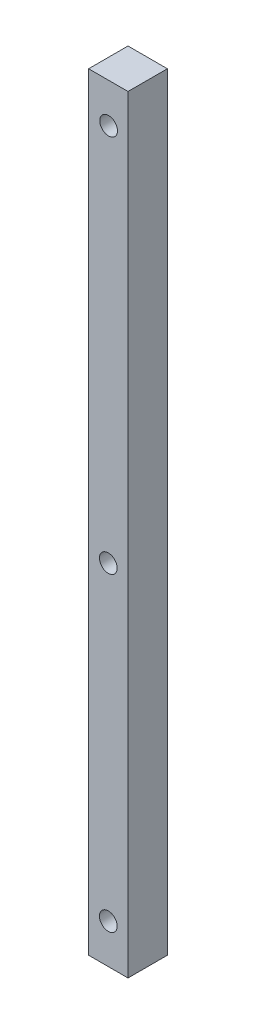
SolidWorks part; units mm, degrees
material "7075-T6, Plate (SS)"
ref_plane "Front Plane" through (0, 0, 0) normal (0, 0, 1) x (1, 0, 0)
ref_plane "Top Plane" through (0, 0, 0) normal (0, 1, 0) x (1, 0, 0)
ref_plane "Right Plane" through (0, 0, 0) normal (1, 0, 0) x (0, 0, -1)
sketch "Sketch1" plane through (0, 0, 0) normal (0, 0, 1) x (1, 0, 0)
  line L1 (-2.5794, -80.0559) -> (2.5006, -80.0559)
  line L2 (-2.5794, -80.0559) -> (-2.5794, -179.0988)
  line L3 (-2.5794, -179.0988) -> (2.5006, -179.0988)
  line L4 (2.5006, -80.0559) -> (2.5006, -179.0988)
  circle A1 centre (-0.0394, -134.0188) radius 1.143
  circle A3 centre (0, -85.1359) radius 1.143
  circle A4 centre (-0.0394, -174.0188) radius 1.143
  dimension "D2" = 2.286
  dimension "D3" = 5.08
  dimension "D4" = 2.286
  dimension "D5" = 40
  dimension "D6" = 2.286
  dimension "D8" = 5.08
  dimension "D7" = 48.8829
  dimension "D1" = 5.08
extrude "Boss-Extrude1" add sketch "Sketch1" along normal blind 5.08
